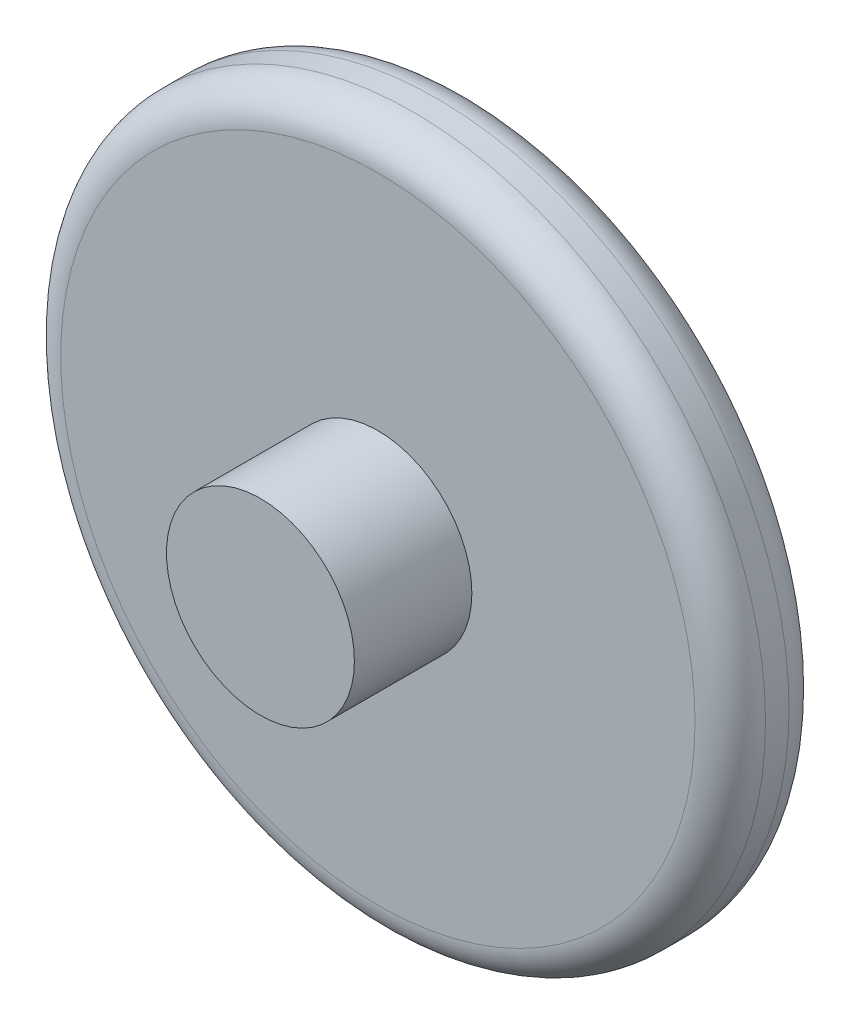
SolidWorks part; units mm, degrees
ref_plane "Alzado" through (0, 0, 0) normal (0, 0, 1) x (1, 0, 0)
ref_plane "Planta" through (0, 0, 0) normal (0, 1, 0) x (1, 0, 0)
ref_plane "Vista lateral" through (0, 0, 0) normal (1, 0, 0) x (0, 0, -1)
sketch "Croquis1" plane through (0, 0, 0) normal (0, 0, 1) x (1, 0, 0)
  circle A0 centre (0, 0) radius 30
extrude "Saliente-Extruir1" add sketch "Croquis1" along normal blind 8
sketch "Croquis2" plane through (0, 0, 8) normal (0, 0, 1) x (1, 0, 0)
  circle A0 centre (0, 0) radius 8
extrude "Saliente-Extruir2" add sketch "Croquis2" along normal blind 10
fillet "Redondeo1" radius 3 2 edges at (30, 0, 0) (30, 0, 8)
